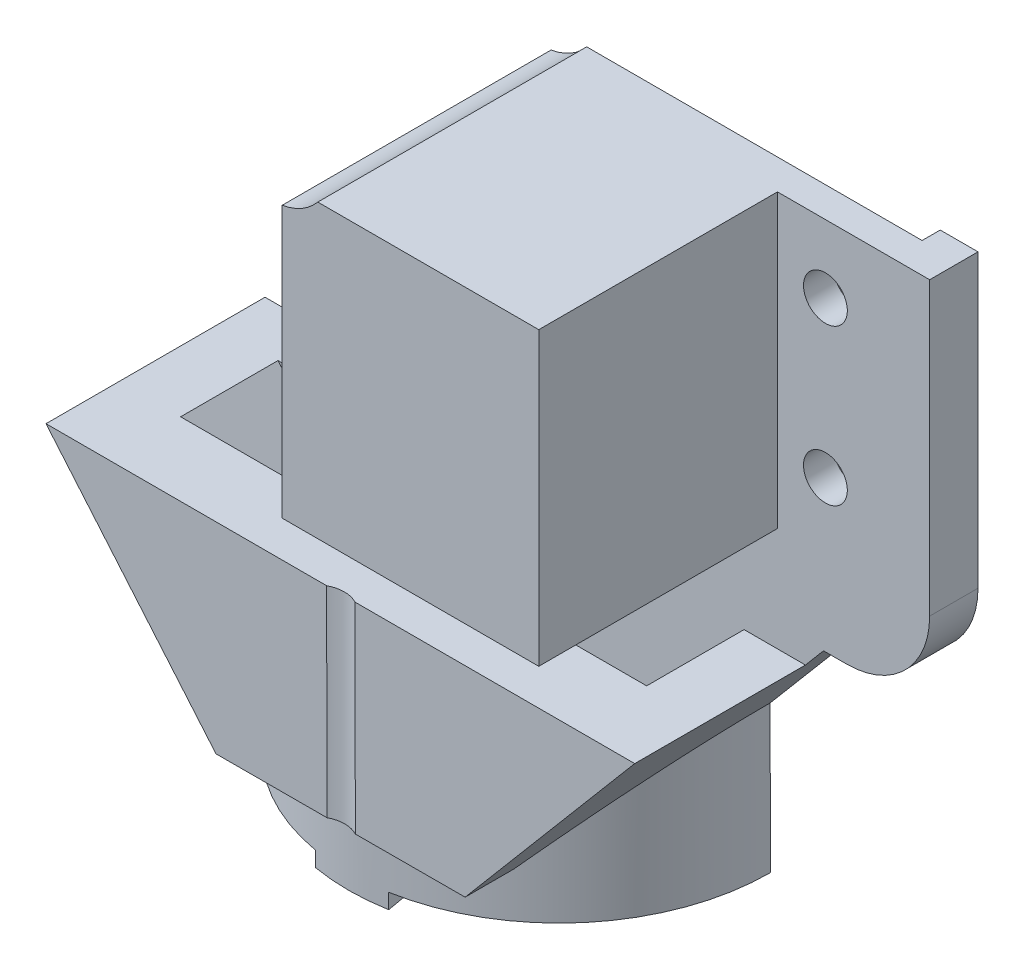
SolidWorks part; units mm, degrees
ref_plane "前基準面" through (0, 0, 0) normal (0, 0, 1) x (1, 0, 0)
ref_plane "上基準面" through (0, 0, 0) normal (0, 1, 0) x (1, 0, 0)
ref_plane "右基準面" through (0, 0, 0) normal (1, 0, 0) x (0, 0, -1)
sketch "草圖2" plane through (0, 0, -1.2) normal (0, 0, 1) x (1, 0, 0)
  line L1 (3.0058, 9.65) -> (27.71, 9.65)
  line L4 (0, 12.135) -> (0, -1.0944) construction
  line L9 (3.0058, -16.55) -> (-19.4856, -16.55)
  line L14 (3.0058, -16.55) -> (7.5474, -16.55)
  line L16 (0.65, 8.2895) -> (0.65, -9.65)
  line L17 (7.5474, -16.55) -> (7.5474, -9.65)
  line L19 (0.65, -9.65) -> (7.5474, -9.65)
  line L23 (-13.9496, -23.0944) -> (-20.6826, -15.135) construction
  line L24 (-13.9496, -23.0944) -> (-8.2328, -29.8525) construction
  line L25 (-8.2328, -29.8525) -> (8.2576, -29.8231) construction
  line L26 (8.2576, -29.8231) -> (13.9504, -23.0934) construction
  line L27 (20.6826, -15.135) -> (13.9504, -23.0934) construction
  line L28 (20.6826, -15.135) -> (22.21, -15.135) construction
  line L29 (27.71, -9.635) -> (27.71, 9.635) construction
  line L30 (-13.9496, -23.0944) -> (-19.4856, -16.55)
  line L31 (-13.9496, -23.0944) -> (-8.2328, -29.8525)
  line L32 (-8.2328, -29.8525) -> (8.2576, -29.8231)
  line L33 (8.2576, -29.8231) -> (13.9504, -23.0934)
  line L34 (20.6826, -15.135) -> (13.9504, -23.0934)
  line L35 (20.6826, -15.135) -> (22.21, -15.135)
  line L36 (27.71, -9.635) -> (27.71, 9.65)
  line L38 (-18.1303, -9.65) -> (15.21, -9.65) construction
  line L40 (15.21, 9.65) -> (-18.1303, 9.65) construction
  circle A0 centre (0, 12.135) radius 3.9 construction
  arc A1 (0.65, 8.2895) -> (3.0058, 9.65) centre (0, 12.135) ccw
  arc A6 (22.21, -15.135) -> (27.71, -9.635) centre (22.21, -9.635) ccw construction
  arc A7 (22.21, -15.135) -> (27.71, -9.635) centre (22.21, -9.635) ccw
  dimension "D1" = 0.65
extrude "填料-伸長1" add sketch "草圖2" along normal blind 14.5
ref_plane "平面1" through (0.0585, -32.8377, 0) normal (0.0018, -1, 0) x (-1, -0.0018, 0)
sketch "草圖6" plane through (0.0585, -32.8377, 0) normal (0.0018, -1, 0) x (-1, -0.0018, 0)
  line L0 (8.2859, 1.2) -> (-8.2044, 1.2) construction
  line L1 (-8.2044, 1.2) -> (-20.6556, 1.2) construction
  line L2 (19.5151, 1.2) -> (8.2859, 1.2) construction
  line L3 (6.0407, 1.2) -> (13.9907, 1.2)
  line L4 (-13.9093, 1.2) -> (-5.9593, 1.2)
  arc A0 (-5.9593, 1.2) -> (6.0407, 1.2) centre (0.0407, 1.2) ccw
  arc A2 (-13.9093, 1.2) -> (13.9907, 1.2) centre (0.0407, 1.2) ccw
  arc A3 (-13.0688, 5.969) -> (-13.9093, 1.2) centre (0.0407, 1.2) ccw construction
extrude "填料-伸長2" add sketch "草圖6" against normal up to next
sketch "草圖8" plane through (0.0532, -29.8377, 0) normal (0.0018, -1, 0) x (1, 0.0018, 0)
  line L0 (-6.0407, -1.2) -> (5.9593, -1.2) construction
  line L1 (5.9593, -1.2) -> (-6.0407, -1.2)
  arc A0 (-6.0407, -1.2) -> (5.9593, -1.2) centre (-0.0407, -1.2) cw
  arc A1 (5.9593, -1.2) -> (-6.0407, -1.2) centre (-0.0407, -1.2) ccw construction
extrude "除料-伸長2" cut sketch "草圖8" against normal blind 6.5
sketch "草圖9" plane through (0, 0, 0) normal (0, 0, 1) x (1, 0, 0)
  line L1 (-15.4252, -16.55) -> (15.4252, -16.55)
  line L2 (7.5474, -16.55) -> (-19.4856, -16.55) construction
  line L13 (-20.3197, 12.135) -> (-29.79, 12.135)
  line L14 (-32.29, 9.635) -> (-32.29, -9.635)
  line L15 (-29.79, -12.135) -> (-20.3197, -12.135)
  line L16 (-18.411, -13.0204) -> (-9.999, -22.9646)
  line L17 (-8.0903, -23.85) -> (8.0903, -23.85)
  line L18 (9.999, -22.9646) -> (18.411, -13.0204)
  line L19 (20.3197, -12.135) -> (22.21, -12.135)
  line L20 (24.71, -9.635) -> (24.71, 9.635)
  line L21 (22.21, 12.135) -> (20.3197, 12.135)
  line L22 (18.411, 13.0204) -> (9.999, 22.9646)
  line L23 (8.0903, 23.85) -> (-8.0903, 23.85)
  line L24 (-9.999, 22.9646) -> (-18.411, 13.0204)
  line L28 (-15.4252, -16.55) -> (-9.999, -22.9646)
  line L29 (-8.0903, -23.85) -> (8.0903, -23.85)
  line L30 (9.999, -22.9646) -> (15.4252, -16.55)
  arc A12 (-20.3197, 12.135) -> (-18.411, 13.0204) centre (-20.3197, 14.635) ccw
  arc A13 (-29.79, 12.135) -> (-32.29, 9.635) centre (-29.79, 9.635) ccw
  arc A14 (-32.29, -9.635) -> (-29.79, -12.135) centre (-29.79, -9.635) ccw
  arc A15 (-18.411, -13.0204) -> (-20.3197, -12.135) centre (-20.3197, -14.635) ccw
  arc A16 (-9.999, -22.9646) -> (-8.0903, -23.85) centre (-8.0903, -21.35) ccw
  arc A17 (8.0903, -23.85) -> (9.999, -22.9646) centre (8.0903, -21.35) ccw
  arc A18 (20.3197, -12.135) -> (18.411, -13.0204) centre (20.3197, -14.635) ccw
  arc A19 (22.21, -12.135) -> (24.71, -9.635) centre (22.21, -9.635) ccw
  arc A20 (24.71, 9.635) -> (22.21, 12.135) centre (22.21, 9.635) ccw
  arc A21 (18.411, 13.0204) -> (20.3197, 12.135) centre (20.3197, 14.635) ccw
  arc A22 (9.999, 22.9646) -> (8.0903, 23.85) centre (8.0903, 21.35) ccw
  arc A23 (-8.0903, 23.85) -> (-9.999, 22.9646) centre (-8.0903, 21.35) ccw
  arc A28 (-9.999, -22.9646) -> (-8.0903, -23.85) centre (-8.0903, -21.35) ccw
  arc A29 (8.0903, -23.85) -> (9.999, -22.9646) centre (8.0903, -21.35) ccw
  dimension "D1" = 0
sketch "草圖10" plane through (0, 0, -1.2) normal (0, 0, -1) x (-1, 0, 0)
  line L0 (15.4252, -16.55) -> (16.0801, -16.55)
  line L1 (15.4252, -16.55) -> (-15.4252, -16.55) construction
  line L2 (-7.5474, -16.55) -> (19.4856, -16.55) construction
  line L3 (8.0495, -26.0434) -> (18.7928, -13.3433) construction
  line L5 (15.4252, -16.55) -> (-7.5474, -16.55)
  line L8 (-7.5474, -16.55) -> (-7.5474, -9.65)
  line L9 (-7.5474, -9.65) -> (-0.65, -9.65)
  line L17 (-0.65, 8.2895) -> (-0.65, -9.65)
  line L18 (16.0801, -16.55) -> (8.0495, -26.0434)
  line L22 (5.4476, -27.2475) -> (-5.4762, -27.228)
  line L34 (-25.21, 9.756) -> (-3.0904, 9.756)
  line L35 (-25.21, 9.756) -> (-25.21, -9.635)
  line L36 (-25.21, -9.635) -> (-25.21, 9.635) construction
  line L37 (-22.21, -12.635) -> (-20.3197, -12.635)
  line L38 (-18.7928, -13.3433) -> (-8.0659, -26.0239)
  arc A1 (-25.21, -9.635) -> (-22.21, -12.635) centre (-22.21, -9.635) ccw construction
  arc A5 (-3.0058, 9.65) -> (-0.65, 8.2895) centre (0, 12.135) ccw construction
  arc A6 (-25.21, -9.635) -> (-22.21, -12.635) centre (-22.21, -9.635) ccw
  arc A7 (-20.3197, -12.635) -> (-18.7928, -13.3433) centre (-20.3197, -14.635) cw
  arc A8 (-3.0904, 9.756) -> (-0.65, 8.2895) centre (0, 12.135) ccw
  arc A15 (-8.0659, -26.0239) -> (-5.4762, -27.228) centre (-5.4701, -23.8281) ccw
  arc A16 (5.4476, -27.2475) -> (8.0495, -26.0434) centre (5.4537, -23.8475) ccw
extrude "除料-伸長4" cut sketch "草圖10" against normal blind 1.2
ref_plane "平面2" through (0, 0, 2) normal (0, 0, -1) x (-1, 0, 0)
sketch "草圖11" plane through (0, 0, 2) normal (0, 0, -1) x (-1, 0, 0)
  line L0 (15.4252, -16.55) -> (9.999, -22.9646) construction
  line L1 (8.0903, -23.85) -> (-8.0903, -23.85) construction
  line L2 (-9.999, -22.9646) -> (-15.4252, -16.55) construction
  line L3 (15.4252, -16.55) -> (-15.4252, -16.55) construction
  line L4 (15.4252, -16.55) -> (9.999, -22.9646)
  line L5 (8.0903, -23.85) -> (-8.0903, -23.85)
  line L6 (-9.999, -22.9646) -> (-15.4252, -16.55)
  line L7 (15.4252, -16.55) -> (-15.4252, -16.55)
  arc A0 (8.0903, -23.85) -> (9.999, -22.9646) centre (8.0903, -21.35) ccw construction
  arc A1 (-9.999, -22.9646) -> (-8.0903, -23.85) centre (-8.0903, -21.35) ccw construction
  arc A2 (8.0903, -23.85) -> (9.999, -22.9646) centre (8.0903, -21.35) ccw
  arc A3 (-9.999, -22.9646) -> (-8.0903, -23.85) centre (-8.0903, -21.35) ccw
extrude "除料-伸長5" cut sketch "草圖11" against normal blind 6.45
sketch "草圖12" plane through (0, 0, 2) normal (0, 0, 1) x (1, 0, 0)
  circle A0 centre (-5.0403, -20.1095) radius 1.45
  circle A1 centre (4.9597, -20.1095) radius 1.45
  dimension "D1" = 2.9
extrude "除料-伸長6" cut sketch "草圖12" against normal up to next
sketch "草圖14" plane through (0.65, 0, 0) normal (-1, 0, 0) x (0, 0, 1)
  line L0 (17, 6) -> (13, 6)
  line L1 (17, 6) -> (17, -6)
  line L2 (13, 6) -> (13, -6)
  line L3 (17, -6) -> (13, -6)
  line L4 (17, 6) -> (13, -6) construction
  line L5 (13, 6) -> (17, -6) construction
  line L7 (0, -9.65) -> (0, 8.2895) construction
  point P1 (15, 0)
  dimension "D1" = 12
  dimension "D2" = 4
  dimension "D3" = 13
sketch "草圖16" plane through (0, 0, 13.3) normal (0, 0, 1) x (1, 0, 0)
  line L5 (27.71, 9.65) -> (17.635, 9.65)
  line L7 (17.635, -9.65) -> (7.5474, -9.65)
  line L8 (7.5474, -9.65) -> (7.5474, -16.55)
  line L9 (7.5474, -16.55) -> (19.4856, -16.55)
  line L10 (8.2576, -29.8231) -> (20.6826, -15.135) construction
  line L11 (20.6826, -15.135) -> (19.4856, -16.55)
  line L12 (20.6826, -15.135) -> (22.21, -15.135) construction
  line L13 (20.6826, -15.135) -> (22.21, -15.135)
  line L14 (27.71, 9.65) -> (27.71, -9.635)
  line L16 (27.71, 9.65) -> (3.0058, 9.65) construction
  line L17 (17.635, 9.65) -> (17.635, -9.65)
  arc A0 (22.21, -15.135) -> (27.71, -9.635) centre (22.21, -9.635) ccw construction
  arc A1 (22.21, -15.135) -> (27.71, -9.635) centre (22.21, -9.635) ccw
  circle A3 centre (20.81, 5.15) radius 1.75 construction
  dimension "D1" = 3.175
extrude "除料-伸長9" cut sketch "草圖16" against normal up to surface (11.3 mm away) up to face at (-3.5903, -20.1095, 2)
sketch "草圖17" plane through (0, 0, 2) normal (0, 0, 1) x (1, 0, 0)
  circle A0 centre (20.81, 5.15) radius 1.45
  circle A1 centre (20.81, -5.15) radius 1.45
  dimension "D1" = 2.9
extrude "除料-伸長10" cut sketch "草圖17" against normal through all and the other way blind 10
sketch "草圖18" plane through (0.0585, -32.8377, 0) normal (0.0018, -1, 0) x (1, 0.0018, 0)
  line L0 (-1.5422, 7.3067) -> (-2.4655, 12.5377) construction
  line L1 (2.3793, 12.5385) -> (1.4578, 7.3072) construction
  line L2 (1.4578, 7.3072) -> (-1.5422, 7.3067) construction
  line L3 (-1.5422, 7.3067) -> (-2.4655, 12.5377)
  line L4 (2.3793, 12.5385) -> (1.4578, 7.3072)
  line L5 (1.4578, 7.3072) -> (-1.5422, 7.3067)
  arc A0 (13.9093, -1.2) -> (-13.9907, -1.2) centre (-0.0407, -1.2) ccw construction
  circle A1 centre (-0.0425, 9.1923) radius 1.2 construction
  arc A2 (2.3793, 12.5385) -> (-2.4655, 12.5377) centre (-0.0407, -1.2) ccw
  circle A3 centre (-0.0425, 9.1923) radius 1.2
extrude "填料-伸長3" add sketch "草圖18" along normal up to surface (1 mm away)
sketch "草圖20" plane through (0.0585, -32.8377, 0) normal (0.0018, -1, 0) x (1, 0.0018, 0)
  circle A0 centre (-0.0425, 9.1923) radius 1.2 construction
  circle A1 centre (-0.0425, 9.1923) radius 1.2
extrude "除料-伸長11" cut sketch "草圖20" against normal up to next
sketch "草圖22" plane through (0, 0, 13.3) normal (0, 0, 1) x (1, 0, 0)
  line L0 (0.65, 8.2895) -> (0.65, -9.65)
  line L4 (0.65, -9.65) -> (17.635, -9.65)
  line L5 (17.635, -9.65) -> (17.635, 9.65)
  line L6 (17.635, 9.65) -> (3.0058, 9.65)
  line L7 (0.65, 8.2895) -> (0.65, -9.65)
  line L8 (0.65, -9.65) -> (17.635, -9.65)
  line L9 (17.635, -9.65) -> (17.635, 9.65)
  line L10 (17.635, 9.65) -> (3.0058, 9.65)
  arc A1 (0.65, 8.2895) -> (3.0058, 9.65) centre (0, 12.135) ccw
  arc A2 (0.65, 8.2895) -> (3.0058, 9.65) centre (0, 12.135) ccw
  dimension "D1" = 0
extrude "填料-伸長4" add sketch "草圖22" along normal blind 4.5
sketch "草圖23" plane through (0.65, 0, 0) normal (-1, 0, 0) x (0, 0, 1)
  line L0 (17, 6) -> (13, 6) construction
  line L1 (17, 6) -> (13, 6)
  line L2 (17, 6) -> (17, -6) construction
  line L3 (17, 6) -> (17, -6)
  line L4 (17, -6) -> (13, -6) construction
  line L5 (17, -6) -> (13, -6)
  line L6 (13, 6) -> (13, -6) construction
  line L7 (13, 6) -> (13, -6)
extrude "除料-伸長13" cut sketch "草圖23" against normal blind 15
sketch "草圖24" plane through (0.0532, -29.8377, 0) normal (0.0018, -1, 0) x (1, 0.0018, 0)
  circle A0 centre (0, 15.0663) radius 2
  point P2 (0, 15.0663)
  dimension "D1" = 4
extrude "除料-伸長14" cut sketch "草圖24" against normal up to surface (13.2842 mm away)
